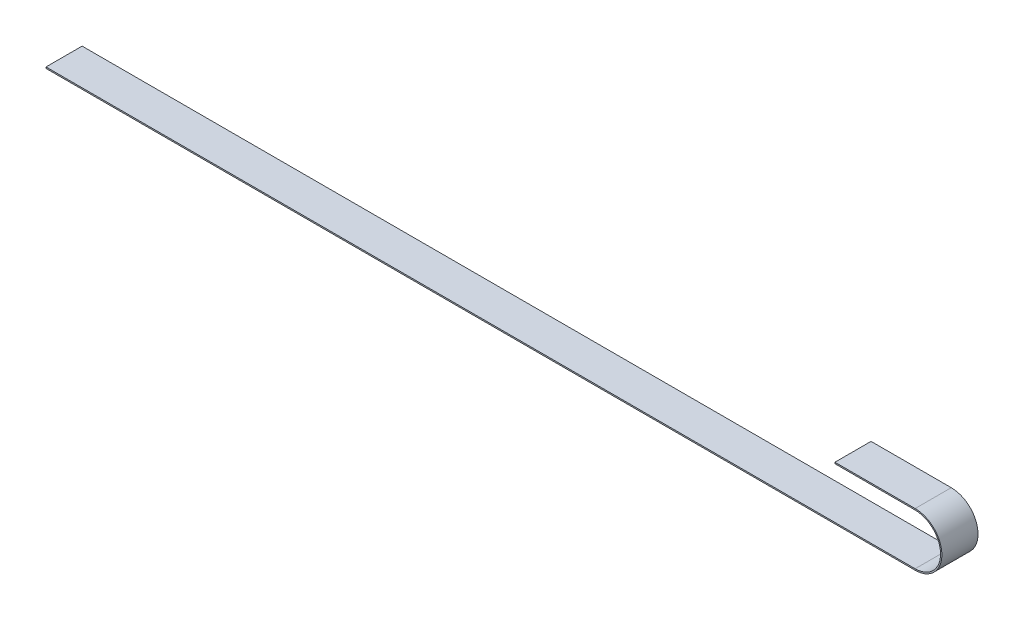
SolidWorks part; units mm, degrees
ref_plane "Front Plane" through (0, 0, 0) normal (0, 0, 1) x (1, 0, 0)
ref_plane "Top Plane" through (0, 0, 0) normal (0, 1, 0) x (1, 0, 0)
ref_plane "Right Plane" through (0, 0, 0) normal (1, 0, 0) x (0, 0, -1)
sketch "Sketch1" plane through (0, 0, 0) normal (0, 0, 1) x (1, 0, 0)
  line L0 (0, 0) -> (650, 0)
  line L1 (650, 40) -> (590, 40)
  arc A0 (650, 0) -> (650, 40) centre (650, 20) ccw
  dimension "D1" = 40
  dimension "D2" = 650
  dimension "D3" = 60
extrude "Extrude-Thin1" add sketch "Sketch1" along normal mid plane 27 thin thin type one direction reverse wall 1
